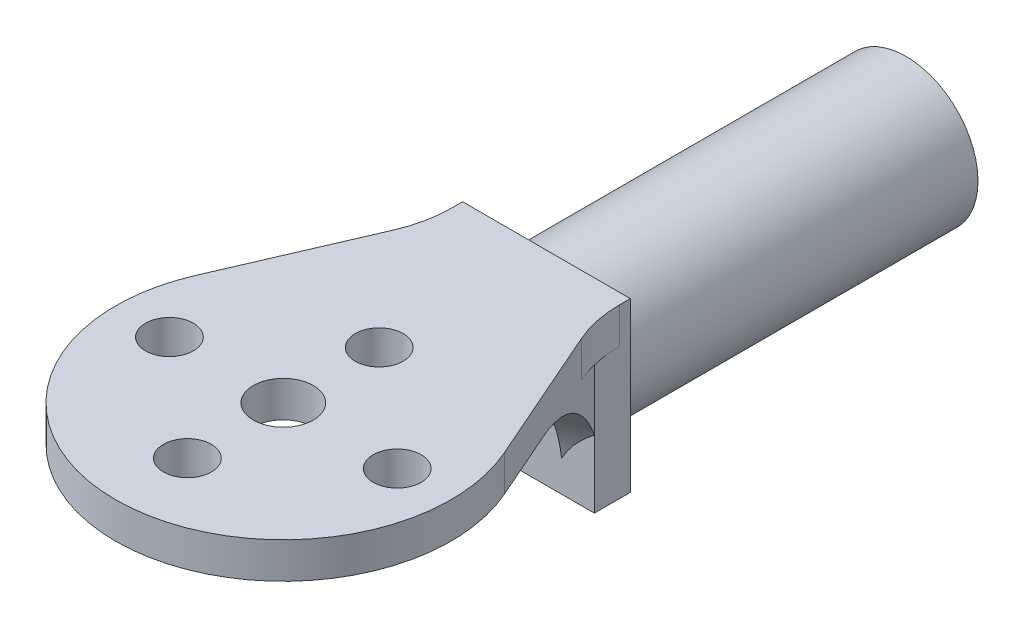
SolidWorks part; units mm, degrees
other "Motor Arm Adapter" parameters "D1"=8.7014, "D3"=10, "D4"=2.4648, "D5"=3.4057, "D6"=4.3257, "D2"=11.8456, "D7"=10.2955, "D8"=2
ref_plane "Front Plane" through (0, 0, 0) normal (0, 0, 1) x (1, 0, 0)
ref_plane "Top Plane" through (0, 0, 0) normal (0, 1, 0) x (1, 0, 0)
ref_plane "Right Plane" through (0, 0, 0) normal (1, 0, 0) x (0, 0, -1)
sketch "Sketch1" plane through (0, 0, 0) normal (0, 0, 1) x (1, 0, 0)
  circle A0 centre (0, 0) radius 6
extrude "Arm Insert" add sketch "Sketch1" along normal blind 30
sketch "Sketch2" plane through (0, 0, 30) normal (0, 0, 1) x (1, 0, 0)
  line L1 (-7, 7) -> (7, 7)
  line L2 (-7, 7) -> (-7, -7)
  line L3 (-7, -7) -> (7, -7)
  line L4 (7, 7) -> (7, -7)
  point P4 (0, 7)
  point P5 (-7, 0)
  dimension "D1" = 14
extrude "Face Plate" add sketch "Sketch2" along normal blind 3
sketch "Sketch3" plane through (0, 7, 0) normal (0, 1, 0) x (1, 0, 0)
  line L0 (7, -33) -> (-7, -33) construction
  line L1 (-7.8177, -34.8958) -> (-12.8034, -46.4554)
  line L2 (7.8436, -34.9215) -> (12.8708, -46.3719)
  line L3 (0.0519, -51.9999) -> (-12.8034, -46.4554) construction
  line L4 (0.0519, -51.9999) -> (12.8708, -46.3719) construction
  line L5 (7, -30.9015) -> (7, -30)
  line L6 (7, -30) -> (-7, -30)
  line L7 (-7, -30) -> (-7, -30.9354)
  circle A0 centre (0.0519, -51.9999) radius 14
  arc A1 (7.8436, -34.9215) -> (7, -30.9015) centre (17, -30.9015) cw
  arc A2 (-7.8177, -34.8958) -> (-7, -30.9354) centre (-17, -30.9354) ccw
  circle A3 centre (0.0519, -51.9999) radius 2.5
  circle A4 centre (0.0519, -43.9999) radius 2
  circle A11 centre (-9.4481, -51.9999) radius 2
  circle A12 centre (0.0519, -59.9999) radius 2
  circle A13 centre (9.5519, -51.9999) radius 2
  point P5 (0, -33)
  point P17 (7, -33)
  point P20 (-7, -33)
  point P33 (0.0519, -51.9999)
  point P34 (0.0519, -51.9999)
  dimension "D1" = 28
  dimension "D5" = 4
  dimension "D6" = 4
  dimension "D2" = 19
  dimension "D4" = 8
  dimension "D7" = 9.5
extrude "Motor Mount" add sketch "Sketch3" against normal blind 3
sketch "Sketch4" plane through (6.0987, 0, 2.6304) normal (-0.9182, 0, -0.396) x (-0.396, 0, 0.9182)
  line L0 (31.6966, -7) -> (31.6966, 4)
  line L1 (41.433, -7) -> (41.433, 4) construction
  line L2 (35.1386, 4) -> (47.7275, 4) construction
  line L3 (33.074, -7) -> (30.3193, -7) construction
  line L4 (31.1782, 4) -> (33.074, 4) construction
  line L5 (31.6966, 4) -> (41.433, 4)
  ellipse E0 centre (41.433, -7) end of major axis (41.433, -18) minor radius 9.7364 (31.6966, -7) -> (41.433, 4) cw
  point P6 (31.6966, -7)
extrude "Motor Mount Support 1" add sketch "Sketch4" against normal blind 2.5
sketch "Sketch5" plane through (-6.2782, 0, 2.7564) normal (0.9156, 0, -0.402) x (-0.402, 0, -0.9156)
  line L0 (-30.2832, -7) -> (-33.0301, -7) construction
  line L1 (-41.3813, 4) -> (-41.3813, -7) construction
  line L2 (-35.1286, 4) -> (-47.634, 4) construction
  line L3 (-41.3813, -7) -> (-33.0301, -7) construction
  line L4 (-31.6566, -7) -> (-31.6566, 4)
  line L6 (-33.0301, 4) -> (-31.1086, 4) construction
  line L7 (-31.6566, 4) -> (-41.3813, 4)
  ellipse E0 centre (-41.3813, -7) end of major axis (-41.3813, -18) minor radius 9.7247 (-31.6566, -7) -> (-41.3813, 4) ccw
  point P8 (-31.6566, -7)
extrude "Motor Mount Support 2" add sketch "Sketch5" against normal blind 2.5
sketch "Sketch8" plane through (0, 0, 0) normal (0, 0, -1) x (-1, 0, 0)
  circle A0 centre (0, 0) radius 2.5
extrude "Lightening Hole" cut sketch "Sketch8" against normal through all
equation "\"D2@Sketch3\"=\"D1@Sketch3\"/2 + 5mm"
equation "\"D6@Sketch3\"=\"D5@Sketch3\""
